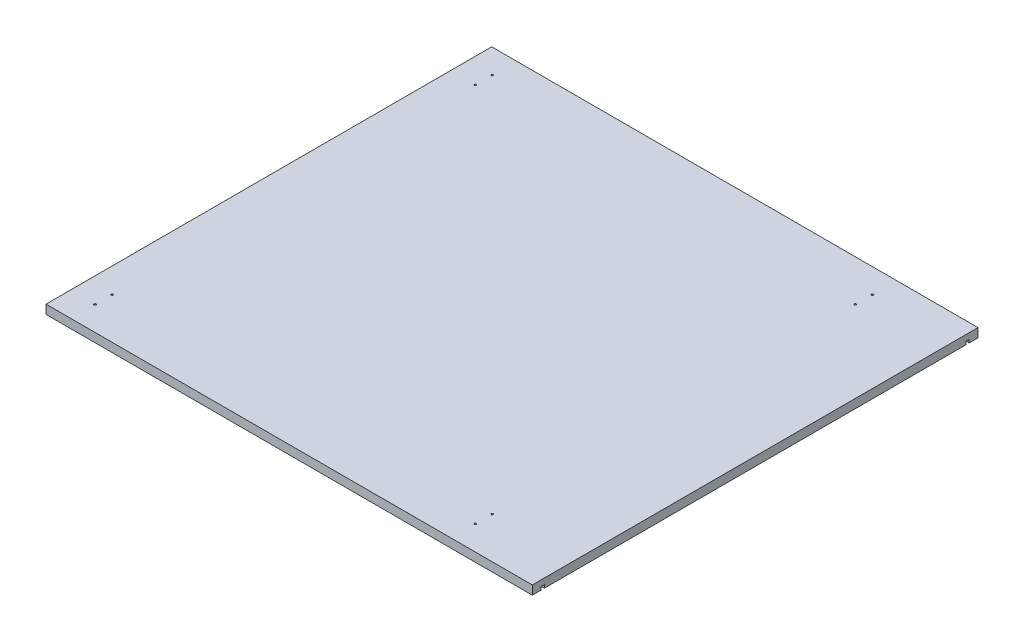
SolidWorks part; units mm, degrees
material "Plywood"
ref_plane "Front Plane" through (0, 0, 0) normal (0, 0, 1) x (1, 0, 0)
ref_plane "Top Plane" through (0, 0, 0) normal (0, 1, 0) x (1, 0, 0)
ref_plane "Right Plane" through (0, 0, 0) normal (1, 0, 0) x (0, 0, -1)
sketch "Sketch1" plane through (0, 0, 0) normal (0, 1, 0) x (1, 0, 0)
  line L1 (-498.856, -457.2) -> (498.856, -457.2)
  line L2 (-498.856, -457.2) -> (-498.856, 457.2)
  line L3 (-498.856, 457.2) -> (498.856, 457.2)
  line L4 (498.856, -457.2) -> (498.856, 457.2)
  line L5 (-498.856, -457.2) -> (498.856, 457.2) construction
  line L6 (-498.856, 457.2) -> (498.856, -457.2) construction
  point P0 (0, 0)
  dimension "D1" = 914.4
  dimension "D2" = 997.712
extrude "Boss-Extrude1" add sketch "Sketch1" along normal blind 18.2562 contours L2 L1 L4 L3
sketch "Sketch2" plane through (0, 18.2562, 0) normal (0, 1, 0) x (1, 0, 0)
  line L0 (-448.056, 390) -> (-448.056, 407.5) construction
  line L5 (-448.056, 390) -> (-58.056, 390) construction
  line L6 (-498.856, -457.2) -> (-498.856, 457.2) construction
  line L7 (-448.056, 390) -> (-448.056, 372.5) construction
  line L8 (-58.056, -395) -> (-58.056, 395) construction
  line L9 (-498.856, 0) -> (498.856, 0) construction
  line L10 (498.856, -457.2) -> (498.856, 457.2) construction
  circle A0 centre (-448.056, 407.5) radius 2
  circle A1 centre (-448.056, 372.5) radius 2
  circle A2 centre (331.944, 372.5) radius 2
  circle A3 centre (331.944, 407.5) radius 2
  circle A8 centre (-448.056, -372.5) radius 2
  circle A9 centre (-448.056, -407.5) radius 2
  circle A10 centre (331.944, -372.5) radius 2
  circle A11 centre (331.944, -407.5) radius 2
  point P0 (0, 0)
  dimension "D1" = 390
  dimension "D2" = 50.8
  dimension "D3" = 17.5
  dimension "D4" = 17.5
extrude "Cut-Extrude1" cut sketch "Sketch2" against normal blind 50.8
sketch "Sketch4" plane through (0, 0, 0) normal (0, -1, 0) x (1, 0, 0)
  line L4 (-480.5997, -438.9438) -> (498.856, -438.9438)
  line L5 (498.856, 457.2) -> (498.856, -457.2) construction
  line L6 (-480.5997, 438.9438) -> (498.856, 438.9438)
  line L7 (-474.2497, -432.5938) -> (498.856, -432.5938)
  line L8 (-480.5997, -438.9438) -> (480.5998, -438.9438)
  line L9 (480.5998, -438.9438) -> (480.5998, 438.9438)
  line L10 (480.5998, 438.9438) -> (-480.5997, 438.9438)
  line L11 (-480.5997, 438.9438) -> (-480.5997, -438.9438)
  line L15 (-480.5997, 438.9438) -> (-480.5997, -438.9438)
  line L16 (-474.2497, 432.5938) -> (-474.2497, -432.5938)
  line L17 (-474.2497, 432.5938) -> (498.856, 432.5938)
  line L18 (498.856, 438.9438) -> (498.856, 432.5938)
  line L19 (498.856, -432.5938) -> (498.856, -438.9438)
  dimension "D1" = 18.2562
  dimension "D2" = 6.35
extrude "Cut-Extrude3" cut sketch "Sketch4" against normal blind 6.35
